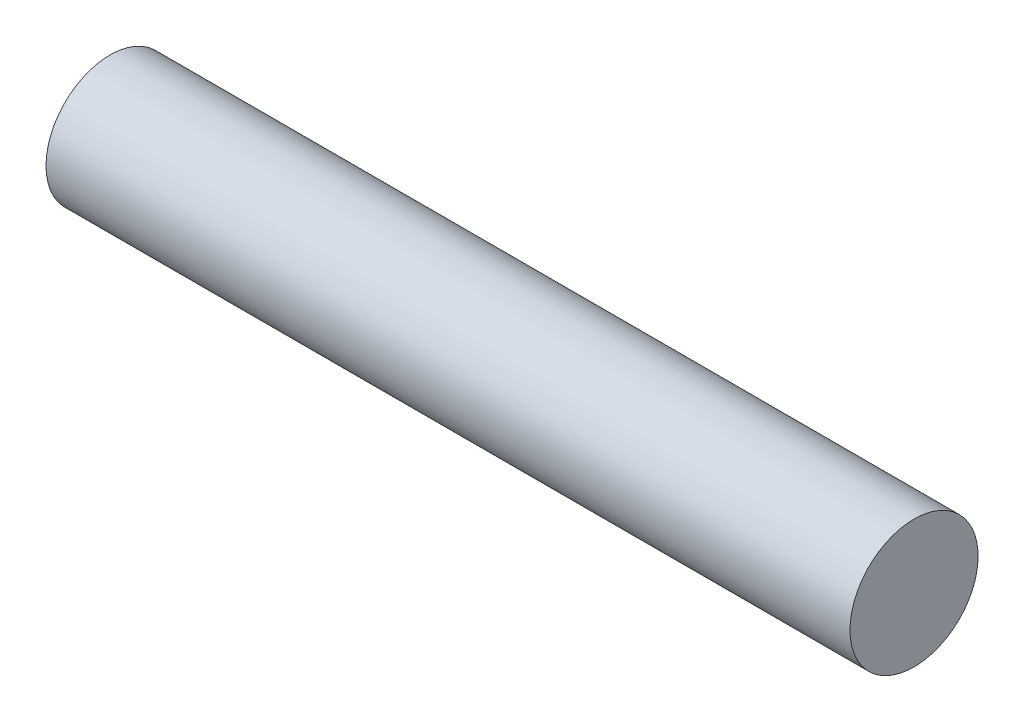
SolidWorks part; units mm, degrees
ref_plane "Front Plane" through (0, 0, 0) normal (0, 0, 1) x (1, 0, 0)
ref_plane "Top Plane" through (0, 0, 0) normal (0, 1, 0) x (1, 0, 0)
ref_plane "Right Plane" through (0, 0, 0) normal (1, 0, 0) x (0, 0, -1)
sketch "Sketch2" plane through (0, 0, 0) normal (0, 1, 0) x (1, 0, 0)
  line L0 (0, 0) -> (800, 0)
  line L1 (800, 0) -> (800, 63.75)
  line L2 (800, 63.75) -> (0, 63.75)
  line L3 (0, 63.75) -> (0, 0)
revolve "Revolve1" add sketch "Sketch2" angle 360 about L2
